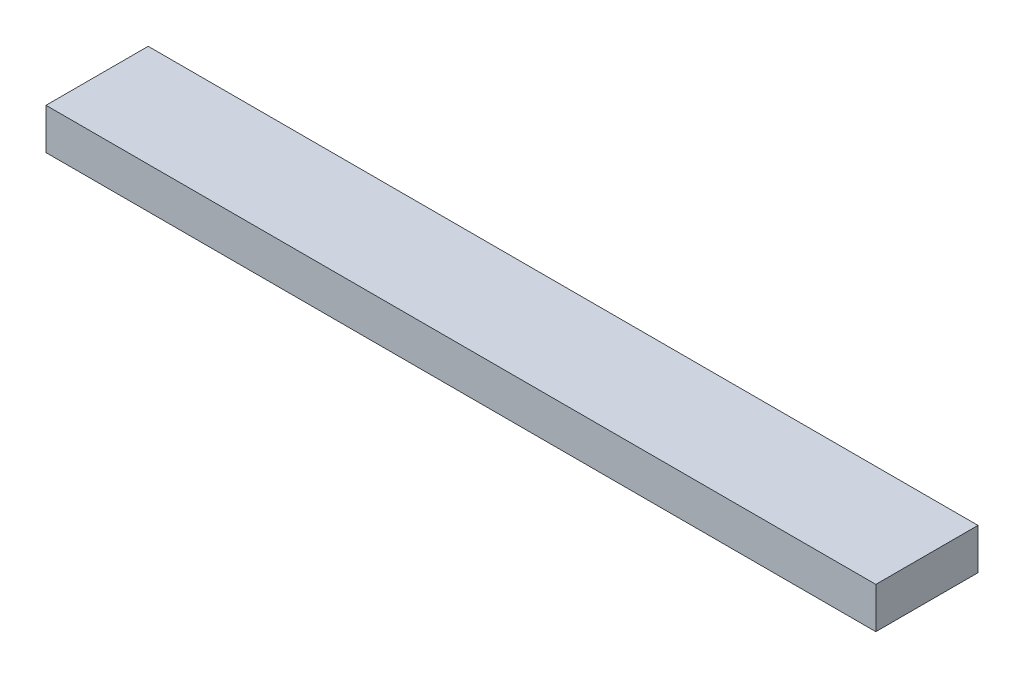
SolidWorks part; units mm, degrees
ref_plane "Front Plane" through (0, 0, 0) normal (0, 0, 1) x (1, 0, 0)
ref_plane "Top Plane" through (0, 0, 0) normal (0, 1, 0) x (1, 0, 0)
ref_plane "Right Plane" through (0, 0, 0) normal (1, 0, 0) x (0, 0, -1)
sketch "Sketch1" plane through (0, 0, 0) normal (0, 1, 0) x (1, 0, 0)
  line L1 (-31.875, 3.925) -> (31.875, 3.925)
  line L2 (-31.875, 3.925) -> (-31.875, -3.925)
  line L3 (-31.875, -3.925) -> (31.875, -3.925)
  line L4 (31.875, 3.925) -> (31.875, -3.925)
  line L5 (-31.875, 3.925) -> (31.875, -3.925) construction
  line L6 (-31.875, -3.925) -> (31.875, 3.925) construction
  point P0 (0, 0)
  dimension "D1" = 63.75
  dimension "D2" = 7.85
extrude "Boss-Extrude1" add sketch "Sketch1" against normal blind 3.15
shell "Shell1" thickness 1.5
sketch "Sketch2" plane through (0, -1.5, 0) normal (0, -1, 0) x (1, 0, 0)
  line L1 (-31.875, -3.925) -> (-31.875, 3.925) construction
  line L2 (31.875, -3.925) -> (-31.875, -3.925) construction
  circle A0 centre (-23.9062, 0) radius 1.5
  circle A1 centre (-23.9062, 0) radius 0.7
  circle A2 centre (-15.9362, 0) radius 1.5
  circle A3 centre (-15.9362, 0) radius 0.7
  circle A4 centre (-7.9662, 0) radius 1.5
  circle A5 centre (-7.9662, 0) radius 0.7
  circle A6 centre (0.0038, 0) radius 1.5
  circle A7 centre (0.0038, 0) radius 0.7
  circle A8 centre (7.9738, 0) radius 1.5
  circle A9 centre (7.9738, 0) radius 0.7
  circle A10 centre (15.9438, 0) radius 1.5
  circle A11 centre (15.9438, 0) radius 0.7
  circle A12 centre (23.9138, 0) radius 1.5
  circle A13 centre (23.9138, 0) radius 0.7
  dimension "D1" = 7.9688
  dimension "D3" = 3
  dimension "D4" = 1.4
  dimension "D6" = 7.97
  dimension "D2" = 3.925
  dimension "D5" = 7
extrude "Boss-Extrude2" add sketch "Sketch2" along normal offset from surface (1.45 mm away) 0.2 up to face at (0, -3.15, 0)
